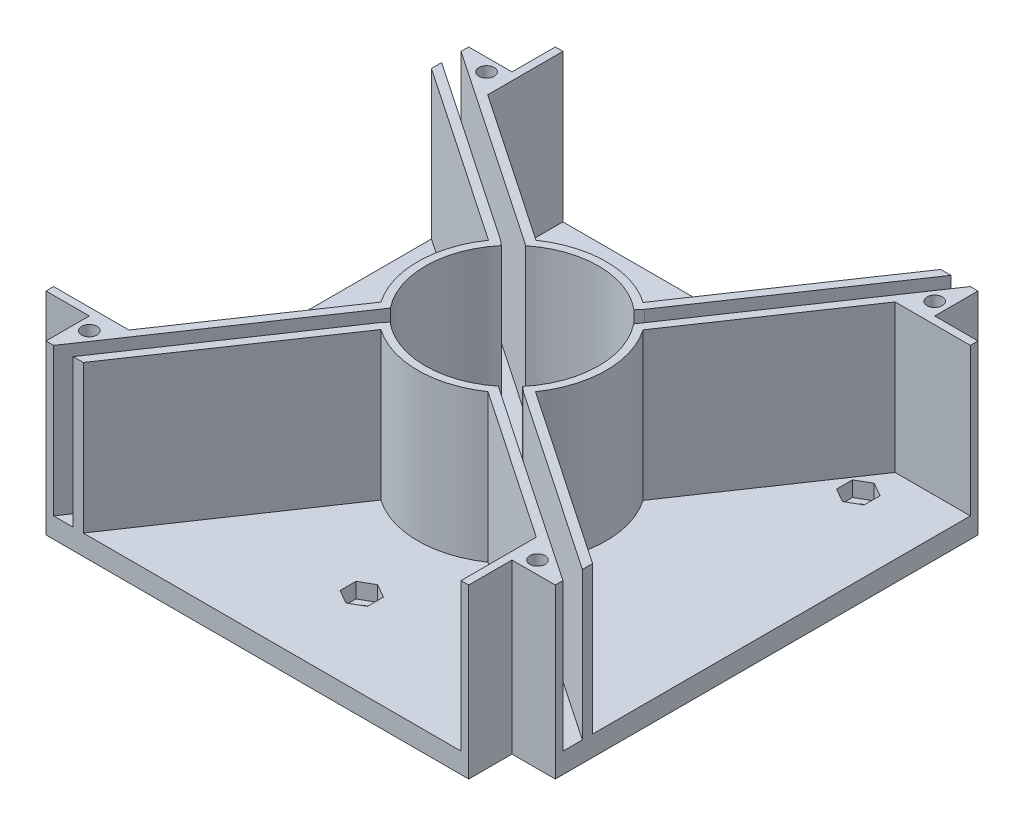
SolidWorks part; units mm, degrees
ref_plane "Front Plane" through (0, 0, 0) normal (0, 0, 1) x (1, 0, 0)
ref_plane "Top Plane" through (0, 0, 0) normal (0, 1, 0) x (1, 0, 0)
ref_plane "Right Plane" through (0, 0, 0) normal (1, 0, 0) x (0, 0, -1)
sketch "Sketch1" plane through (0, 0, 0) normal (0, 1, 0) x (1, 0, 0)
  line L0 (0, -50) -> (0, 50) construction
  line L1 (-50, 0) -> (50, 0) construction
  line L2 (-55, 0) -> (55, 0) construction
  line L3 (0, -55) -> (0, 55) construction
  line L5 (50, 50) -> (-50, 50)
  line L6 (50, 50) -> (50, -50)
  line L7 (50, -50) -> (-50, -50)
  line L8 (-50, 50) -> (-50, -50)
  point P10 (0, 0)
extrude "Boss-Extrude1" add sketch "Sketch1" along normal blind 4
sketch "Sketch2" plane through (0, 4, 0) normal (0, 1, 0) x (1, 0, 0)
  circle A0 centre (0, 0) radius 4.7625
extrude "Cut-Extrude1" cut sketch "Sketch2" against normal through all contours A0
sketch "Sketch3" plane through (0, 4, 0) normal (0, 1, 0) x (1, 0, 0)
  line L0 (0, -2.2) -> (0, 2.2) construction
  line L1 (-50, 50) -> (-41.5, 50)
  line L2 (-50, 50) -> (-50, 41.5)
  line L3 (-50, 41.5) -> (-41.5, 41.5)
  line L4 (-41.5, 50) -> (-41.5, 41.5)
  line L5 (50, 41.5) -> (41.5, 41.5)
  line L6 (41.5, 50) -> (41.5, 41.5)
  line L7 (50, 50) -> (41.5, 50)
  line L8 (50, 50) -> (50, 41.5)
  line L9 (-2.2, 0) -> (2.2, 0) construction
  line L10 (50, -50) -> (50, -41.5)
  line L11 (50, -50) -> (41.5, -50)
  line L12 (41.5, -50) -> (41.5, -41.5)
  line L13 (50, -41.5) -> (41.5, -41.5)
  line L14 (-50, -41.5) -> (-41.5, -41.5)
  line L15 (-41.5, -50) -> (-41.5, -41.5)
  line L16 (-50, -50) -> (-41.5, -50)
  line L17 (-50, -50) -> (-50, -41.5)
extrude "Cut-Extrude2" cut sketch "Sketch3" against normal through all
sketch "Sketch4" plane through (0, 4, 0) normal (0, 1, 0) x (1, 0, 0)
  line L0 (0, -2.2) -> (0, 2.2) construction
  line L1 (-10.9274, -13.0228) -> (-11.8916, -14.1718)
  line L2 (10.9274, -13.0228) -> (11.8916, -14.1718)
  line L3 (-13.0228, -10.9274) -> (-14.1718, -11.8916)
  line L4 (-13.0228, 10.9274) -> (-14.1718, 11.8916)
  line L5 (-10.9274, 13.0228) -> (-11.8916, 14.1718)
  line L6 (10.9274, 13.0228) -> (11.8916, 14.1718)
  line L7 (13.0228, 10.9274) -> (14.1718, 11.8916)
  line L8 (13.0228, -10.9274) -> (14.1718, -11.8916)
  line L9 (0, 0) -> (0, -17) construction
  circle A0 centre (0, 0) radius 17 construction
  arc A2 (-10.9274, -13.0228) -> (10.9274, -13.0228) centre (0, 0) ccw
  arc A3 (-11.8916, -14.1718) -> (11.8916, -14.1718) centre (0, 0) ccw
  arc A4 (-13.0228, 10.9274) -> (-13.0228, -10.9274) centre (0, 0) ccw
  arc A5 (-14.1718, 11.8916) -> (-14.1718, -11.8916) centre (0, 0) ccw
  arc A6 (10.9274, 13.0228) -> (-10.9274, 13.0228) centre (0, 0) ccw
  arc A7 (11.8916, 14.1718) -> (-11.8916, 14.1718) centre (0, 0) ccw
  arc A8 (13.0228, -10.9274) -> (13.0228, 10.9274) centre (0, 0) ccw
  arc A9 (14.1718, -11.8916) -> (14.1718, 11.8916) centre (0, 0) ccw
  dimension "D1" = 4
  dimension "D2" = 17
extrude "Boss-Extrude3" add sketch "Sketch4" along normal blind 29
sketch "Sketch7" plane through (0, 4, 0) normal (0, 1, 0) x (1, 0, 0)
  line L0 (-41.5, -41.5) -> (-41.5, -50)
  line L1 (-41.5, -50) -> (-40, -50)
  line L2 (-41.5, -50) -> (41.5, -50) construction
  line L3 (-41.5, -41.5) -> (-50, -41.5)
  line L4 (-50, -41.5) -> (-50, -40)
  line L5 (-50, 41.5) -> (-50, -41.5) construction
  line L6 (-40, -50) -> (-40, -40)
  line L7 (-40, -40) -> (-50, -40)
  line L8 (0, -18.15) -> (0, 18.15) construction
  line L9 (40, -50) -> (40, -40)
  line L10 (50, -41.5) -> (50, -40)
  line L11 (41.5, -41.5) -> (50, -41.5)
  line L12 (41.5, -41.5) -> (41.5, -50)
  line L13 (41.5, -50) -> (40, -50)
  line L14 (40, -40) -> (50, -40)
  line L15 (-18.15, 0) -> (18.15, 0) construction
  line L16 (50, 41.5) -> (50, 40)
  line L17 (40, 50) -> (40, 40)
  line L18 (40, 40) -> (50, 40)
  line L19 (41.5, 41.5) -> (50, 41.5)
  line L20 (41.5, 50) -> (40, 50)
  line L21 (41.5, 41.5) -> (41.5, 50)
  line L22 (-50, 41.5) -> (-50, 40)
  line L23 (-41.5, 41.5) -> (-50, 41.5)
  line L24 (-40, 40) -> (-50, 40)
  line L25 (-40, 50) -> (-40, 40)
  line L26 (-41.5, 50) -> (-40, 50)
  line L27 (-41.5, 41.5) -> (-41.5, 50)
extrude "Boss-Extrude4" add sketch "Sketch7" along normal blind 29
sketch "Sketch8" plane through (0, 4, 0) normal (0, 1, 0) x (1, 0, 0)
  line L11 (-14.1718, -11.8916) -> (-40, -50)
  line L12 (-11.8916, -14.1718) -> (-36.1743, -50)
  line L13 (-40, -50) -> (40, -50) construction
  line L14 (-36.1743, -50) -> (-40, -50)
  line L15 (-14.1718, -11.8916) -> (-12.4887, -9.4082)
  line L16 (-11.8916, -14.1718) -> (-9.8672, -11.1849)
  line L17 (-9.8672, -11.1849) -> (-12.4887, -9.4082)
  line L18 (-11.8916, 14.1718) -> (-50, 40)
  line L19 (-14.1718, 11.8916) -> (-50, 36.1743)
  line L20 (-50, 40) -> (-50, -40) construction
  line L21 (-50, 40) -> (-50, 36.1743)
  line L22 (-11.8916, 14.1718) -> (-9.4082, 12.4887)
  line L23 (-14.1718, 11.8916) -> (-11.1849, 9.8672)
  line L24 (-11.1849, 9.8672) -> (-9.4082, 12.4887)
  line L25 (14.1718, 11.8916) -> (40, 50)
  line L26 (11.8916, 14.1718) -> (36.1743, 50)
  line L27 (40, 50) -> (-40, 50) construction
  line L28 (36.1743, 50) -> (40, 50)
  line L29 (14.1718, 11.8916) -> (12.4887, 9.4082)
  line L30 (11.8916, 14.1718) -> (9.8672, 11.1849)
  line L31 (9.8672, 11.1849) -> (12.4887, 9.4082)
  line L32 (11.8916, -14.1718) -> (50, -40)
  line L33 (14.1718, -11.8916) -> (50, -36.1743)
  line L34 (50, -40) -> (50, 40) construction
  line L35 (50, -36.1743) -> (50, -40)
  line L36 (11.8916, -14.1718) -> (9.4082, -12.4887)
  line L37 (14.1718, -11.8916) -> (11.1849, -9.8672)
  line L38 (11.1849, -9.8672) -> (9.4082, -12.4887)
extrude "Cut-Extrude4" cut sketch "Sketch8" along normal through all
sketch "Sketch9" plane through (0, 4, 0) normal (0, 1, 0) x (1, 0, 0)
  line L0 (-11.8916, -14.1718) -> (-36.1743, -50)
  line L1 (-36.1743, -50) -> (-34.1743, -50)
  line L2 (-40, -50) -> (40, -50) construction
  line L5 (-14.1718, -11.8916) -> (-40, -50)
  line L6 (-34.1743, -50) -> (-10.5211, -15.1007)
  line L7 (-10.5211, -15.1007) -> (-11.8916, -14.1718)
  line L8 (-40, -50) -> (-42, -50) construction
  line L9 (-42, -50) -> (-40, -47.0491) construction
  line L10 (-40, -50) -> (-40, -40) construction
  line L11 (-40, -47.0491) -> (-14.9813, -10.1349)
  line L12 (-14.9813, -10.1349) -> (-13.6108, -11.0638)
  line L13 (-14.1718, -11.8916) -> (-12.4887, -9.4082) construction
  line L14 (-13.6108, -11.0638) -> (-14.1718, -11.8916)
  line L15 (-40, -47.0491) -> (-40, -50)
  line L16 (-50, 34.1743) -> (-15.1007, 10.5211)
  line L17 (-50, 36.1743) -> (-50, 34.1743)
  line L18 (-14.1718, 11.8916) -> (-50, 36.1743)
  line L19 (-11.8916, 14.1718) -> (-50, 40)
  line L20 (-47.0491, 40) -> (-10.1349, 14.9813)
  line L21 (-15.1007, 10.5211) -> (-14.1718, 11.8916)
  line L22 (-11.0638, 13.6108) -> (-11.8916, 14.1718)
  line L23 (-10.1349, 14.9813) -> (-11.0638, 13.6108)
  line L24 (-50, 42) -> (-47.0491, 40) construction
  line L25 (-50, 40) -> (-50, 42) construction
  line L26 (-47.0491, 40) -> (-50, 40)
  line L27 (34.1743, 50) -> (10.5211, 15.1007)
  line L28 (36.1743, 50) -> (34.1743, 50)
  line L29 (11.8916, 14.1718) -> (36.1743, 50)
  line L30 (14.1718, 11.8916) -> (40, 50)
  line L31 (40, 47.0491) -> (14.9813, 10.1349)
  line L32 (10.5211, 15.1007) -> (11.8916, 14.1718)
  line L33 (13.6108, 11.0638) -> (14.1718, 11.8916)
  line L34 (14.9813, 10.1349) -> (13.6108, 11.0638)
  line L35 (42, 50) -> (40, 47.0491) construction
  line L36 (40, 50) -> (42, 50) construction
  line L37 (40, 47.0491) -> (40, 50)
  line L38 (50, -34.1743) -> (15.1007, -10.5211)
  line L39 (50, -36.1743) -> (50, -34.1743)
  line L40 (14.1718, -11.8916) -> (50, -36.1743)
  line L41 (11.8916, -14.1718) -> (50, -40)
  line L42 (47.0491, -40) -> (10.1349, -14.9813)
  line L43 (15.1007, -10.5211) -> (14.1718, -11.8916)
  line L44 (11.0638, -13.6108) -> (11.8916, -14.1718)
  line L45 (10.1349, -14.9813) -> (11.0638, -13.6108)
  line L46 (50, -42) -> (47.0491, -40) construction
  line L47 (50, -40) -> (50, -42) construction
  line L48 (47.0491, -40) -> (50, -40)
  dimension "D1" = 1.6556
  dimension "D2" = 1.6556
  dimension "D3" = 4
extrude "Boss-Extrude5" add sketch "Sketch9" along normal blind 29
sketch "Sketch11" plane through (0, 4, 0) normal (0, 1, 0) x (1, 0, 0)
  line L0 (-40, -40) -> (-35.2225, -40)
  line L1 (-15.2301, -10.5021) -> (-40, -47.0491) construction
  line L2 (-35.2225, -40) -> (-40, -47.0491)
  line L3 (-40, -47.0491) -> (-40, -40)
  line L4 (-40, 40) -> (-40, 35.2225)
  line L5 (-47.0491, 40) -> (-40, 40)
  line L6 (-40, 35.2225) -> (-47.0491, 40)
  line L7 (40, 40) -> (35.2225, 40)
  line L8 (40, 47.0491) -> (40, 40)
  line L9 (35.2225, 40) -> (40, 47.0491)
  line L10 (40, -40) -> (40, -35.2225)
  line L11 (47.0491, -40) -> (40, -40)
  line L12 (40, -35.2225) -> (47.0491, -40)
  dimension "D1" = 4
extrude "Boss-Extrude6" add sketch "Sketch11" along normal blind 29
sketch "Sketch12" plane through (0, 0, 0) normal (0, -1, 0) x (-1, 0, 0)
  line L0 (0, 0) -> (-3.5, 0) construction
  line L1 (-3.5, 0) -> (-3.5, 33) construction
  line L2 (-3.5, 33) -> (-35, 33) construction
  line L3 (-18.15, 0) -> (18.15, 0) construction
  line L4 (-3.5, 0) -> (-3.5, -33) construction
  line L5 (-35, 33) -> (-35, -33) construction
  line L6 (-35, -33) -> (-28, -33) construction
  circle A0 centre (-3.5, 33) radius 1.5
  circle A3 centre (-3.5, -33) radius 1.5
  circle A6 centre (-35, 33) radius 1.5
  circle A7 centre (-28, -33) radius 1.5
extrude "Cut-Extrude5" cut sketch "Sketch12" against normal through all
sketch "Sketch14" plane through (0, 4, 0) normal (0, 1, 0) x (1, 0, 0)
  line L1 (28, -29.8823) -> (25.3, -31.4412)
  line L2 (25.3, -31.4412) -> (25.3, -34.5588)
  line L3 (25.3, -34.5588) -> (28, -36.1177)
  line L4 (28, -36.1177) -> (30.7, -34.5588)
  line L5 (30.7, -34.5588) -> (30.7, -31.4412)
  line L6 (30.7, -31.4412) -> (28, -29.8823)
  line L7 (3.5, -29.8823) -> (0.8, -31.4412)
  line L8 (0.8, -31.4412) -> (0.8, -34.5588)
  line L9 (0.8, -34.5588) -> (3.5, -36.1177)
  line L10 (3.5, -36.1177) -> (6.2, -34.5588)
  line L11 (6.2, -34.5588) -> (6.2, -31.4412)
  line L12 (6.2, -31.4412) -> (3.5, -29.8823)
  line L13 (3.5, 36.1177) -> (0.8, 34.5588)
  line L14 (0.8, 34.5588) -> (0.8, 31.4412)
  line L15 (0.8, 31.4412) -> (3.5, 29.8823)
  line L16 (3.5, 29.8823) -> (6.2, 31.4412)
  line L17 (6.2, 31.4412) -> (6.2, 34.5588)
  line L18 (6.2, 34.5588) -> (3.5, 36.1177)
  line L19 (35, 36.1177) -> (32.3, 34.5588)
  line L20 (32.3, 34.5588) -> (32.3, 31.4412)
  line L21 (32.3, 31.4412) -> (35, 29.8823)
  line L22 (35, 29.8823) -> (37.7, 31.4412)
  line L23 (37.7, 31.4412) -> (37.7, 34.5588)
  line L24 (37.7, 34.5588) -> (35, 36.1177)
  circle A0 centre (28, -33) radius 2.7 construction
  circle A1 centre (3.5, -33) radius 2.7 construction
  circle A2 centre (3.5, 33) radius 2.7 construction
  circle A3 centre (35, 33) radius 2.7 construction
extrude "Cut-Extrude6" cut sketch "Sketch14" against normal blind 3
sketch "Sketch15" plane through (0, 33, 0) normal (0, 1, 0) x (1, 0, 0)
  line L0 (41.5, -41.5) -> (41.5, -39) construction
  line L1 (41.5, -39) -> (44, -39) construction
  circle A0 centre (44, -39) radius 1.5
  circle A1 centre (-39, -44) radius 1.5
  circle A2 centre (-44, 39) radius 1.5
  circle A3 centre (39, 44) radius 1.5
  dimension "D1" = 4
extrude "Cut-Extrude7" cut sketch "Sketch15" against normal blind 10
